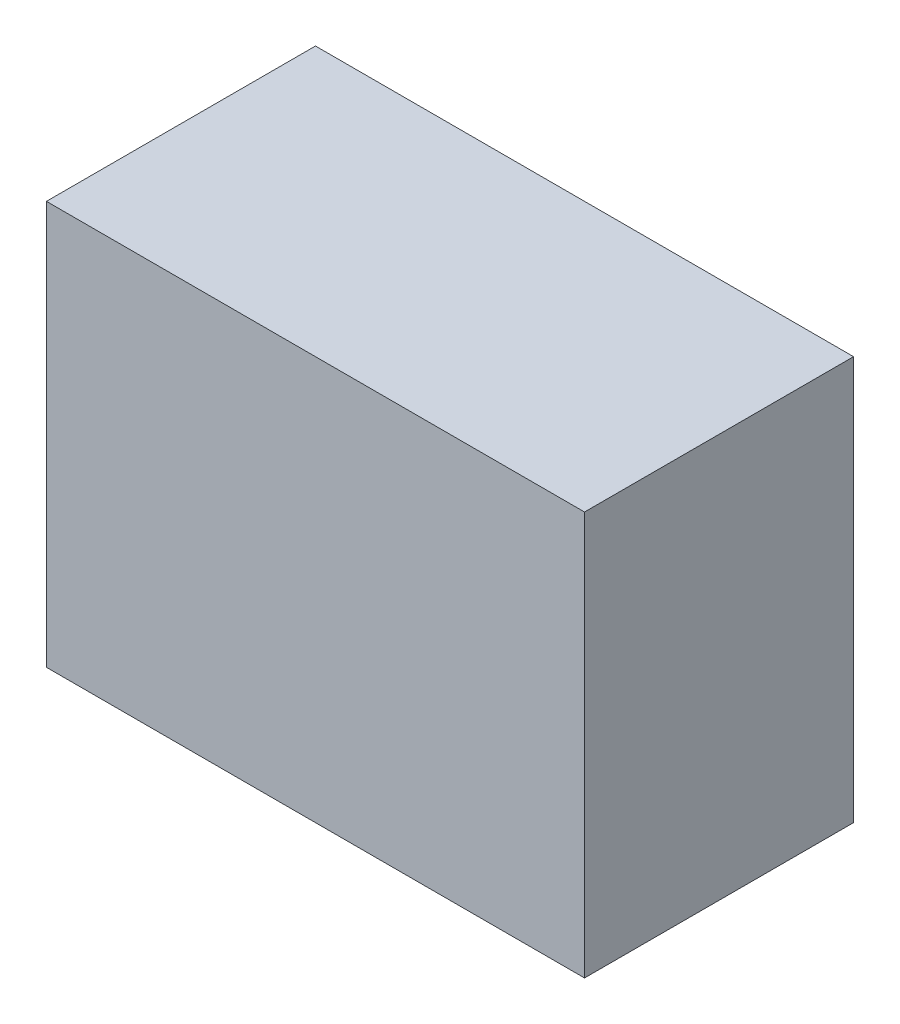
SolidWorks part; units mm, degrees
ref_plane "Front Plane" through (0, 0, 0) normal (0, 0, 1) x (1, 0, 0)
ref_plane "Top Plane" through (0, 0, 0) normal (0, 1, 0) x (1, 0, 0)
ref_plane "Right Plane" through (0, 0, 0) normal (1, 0, 0) x (0, 0, -1)
sketch "Sketch1" plane through (0, 0, 0) normal (0, 0, 1) x (1, 0, 0)
  line L1 (-200, 150) -> (200, 150)
  line L2 (-200, 150) -> (-200, -150)
  line L3 (-200, -150) -> (200, -150)
  line L4 (200, 150) -> (200, -150)
  line L5 (-200, 150) -> (200, -150) construction
  line L6 (-200, -150) -> (200, 150) construction
  point P0 (0, 0)
  dimension "D1" = 400
  dimension "D2" = 300
extrude "Boss-Extrude1" add sketch "Sketch1" against normal blind 200
sketch "Sketch2" plane through (0, 0, 0) normal (0, 0, 1) x (1, 0, 0)
  line L0 (200, -150) -> (200, 150) construction
  line L1 (200, 150) -> (-200, 150) construction
  line L2 (-200, 150) -> (-200, -150) construction
  circle A0 centre (150, 75) radius 11
  circle A1 centre (75, 75) radius 11
  circle A2 centre (75, 0) radius 11
  circle A3 centre (75, -75) radius 11
  circle A4 centre (150, 0) radius 11
  circle A5 centre (150, -75) radius 11
  circle A6 centre (0, 0) radius 11
  circle A7 centre (-150, 75) radius 11
  circle A8 centre (-150, 0) radius 11
  circle A9 centre (-150, -75) radius 11
  circle A10 centre (-70, 0) radius 11
  dimension "D1" = 22
  dimension "D2" = 50
  dimension "D3" = 75
  dimension "D6" = 75
  dimension "D7" = 50
  dimension "D4" = 2
  dimension "D5" = 3
  dimension "D8" = 3
  dimension "D9" = 2
